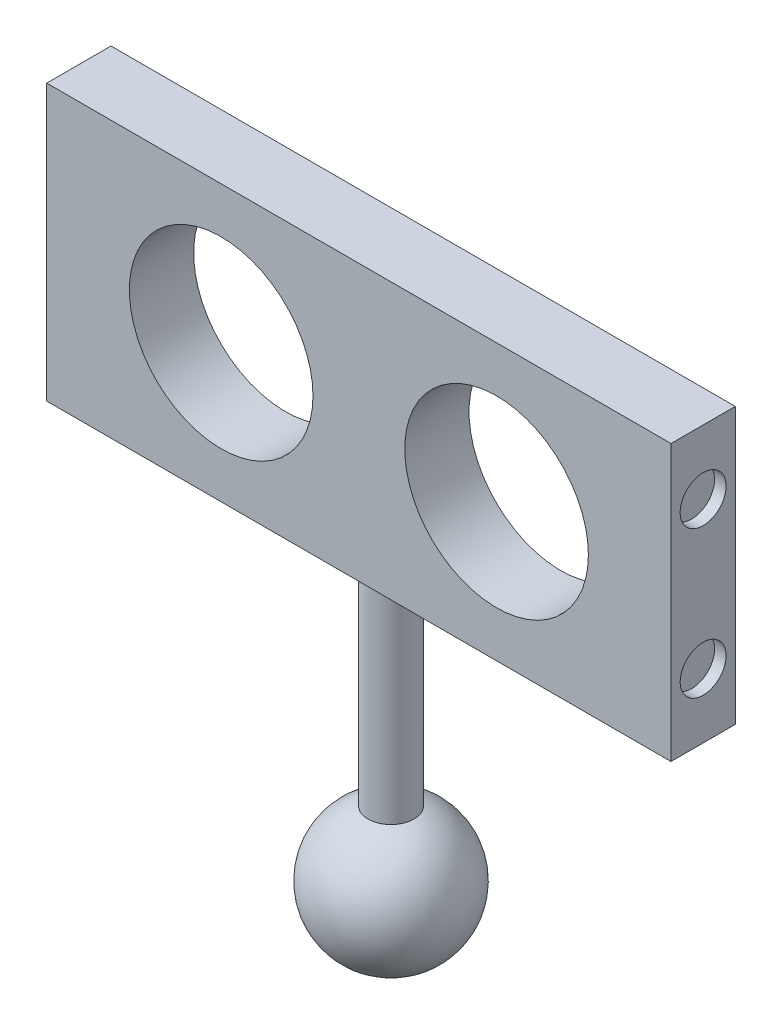
SolidWorks part; units mm, degrees
material "ABS"
ref_plane "Front Plane" through (0, 0, 0) normal (0, 0, 1) x (1, 0, 0)
ref_plane "Top Plane" through (0, 0, 0) normal (0, 1, 0) x (1, 0, 0)
ref_plane "Right Plane" through (0, 0, 0) normal (1, 0, 0) x (0, 0, -1)
sketch "Sketch1" plane through (0, 0, 0) normal (0, 1, 0) x (1, 0, 0)
  line L1 (-43.18, 4.445) -> (43.18, 4.445)
  line L2 (-43.18, 4.445) -> (-43.18, -4.445)
  line L3 (-43.18, -4.445) -> (43.18, -4.445)
  line L4 (43.18, 4.445) -> (43.18, -4.445)
  line L5 (-43.18, 4.445) -> (43.18, -4.445) construction
  line L6 (-43.18, -4.445) -> (43.18, 4.445) construction
  point P0 (0, 0)
  dimension "D1" = 8.89
  dimension "D2" = 86.36
extrude "Boss-Extrude1" add sketch "Sketch1" along normal blind 38.1
sketch "Sketch2" plane through (0, 0, 4.445) normal (0, 0, 1) x (1, 0, 0)
  line L0 (0, 0) -> (0, 38.1) construction
  line L1 (-43.18, 38.1) -> (43.18, 38.1) construction
  line L2 (-19.05, 19.05) -> (19.05, 19.05)
  circle A0 centre (19.05, 19.05) radius 12.7
  circle A1 centre (-19.05, 19.05) radius 12.7
  point P8 (0, 19.05)
  dimension "D2" = 25.4
  dimension "D1" = 38.1
extrude "Cut-Extrude1" cut sketch "Sketch2" against normal through all
sketch "Sketch3" plane through (0, 0, 0) normal (0, -1, 0) x (1, 0, 0)
  circle A0 centre (0, 0) radius 3.175
extrude "Boss-Extrude2" add sketch "Sketch3" along normal blind 38.1 contours A0
sketch "Sketch4" plane through (0, -38.1, 0) normal (0, -1, 0) x (1, 0, 0)
  line L0 (0, -9.525) -> (0, 9.525)
  arc A0 (0, 9.525) -> (0, -9.525) centre (0, 0) cw
  point P5 (0, 0)
revolve "Revolve1" add sketch "Sketch4" angle 360 about L0
sketch "Sketch5" plane through (43.18, 0, 0) normal (1, 0, 0) x (0, 0, -1)
  line L0 (0, 38.1) -> (0, 0) construction
  line L2 (-4.445, 38.1) -> (4.445, 38.1) construction
  line L3 (-4.445, 0) -> (4.445, 0) construction
  line L5 (0, 19.05) -> (11.004, 19.05) construction
  circle A2 centre (0, 29.21) radius 3.175
  circle A3 centre (0, 8.89) radius 3.175
  point P11 (0, 0)
  point P12 (0, 0)
  dimension "D1" = 6.35
  dimension "D2" = 10.16
extrude "Cut-Extrude2" cut sketch "Sketch5" against normal blind 1.5875
mirror "Mirror1" about plane through (0, 0, 0) normal (1, 0, 0) of "Cut-Extrude2"
